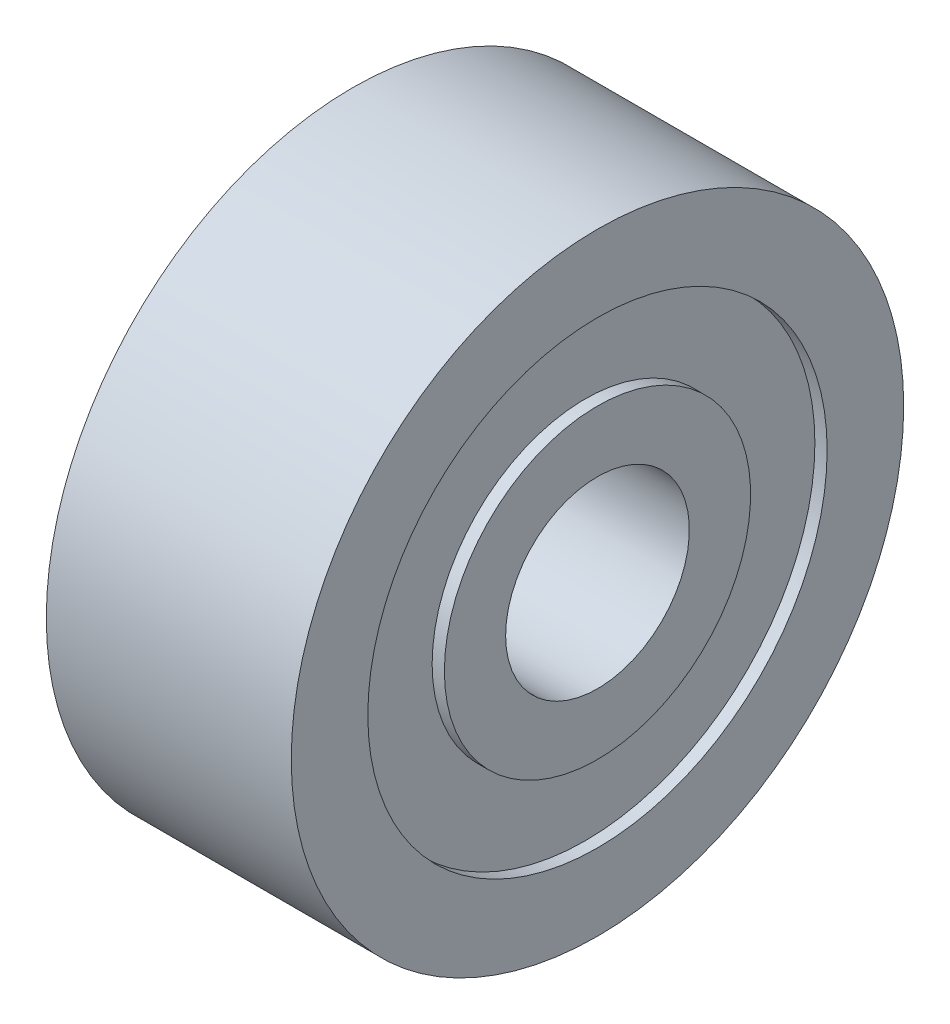
SolidWorks part; units mm, degrees
material "Acier allié"
ref_plane "Plan de face" through (0, 0, 0) normal (0, 0, 1) x (1, 0, 0)
ref_plane "Plan de dessus" through (0, 0, 0) normal (0, 1, 0) x (1, 0, 0)
ref_plane "Plan de droite" through (0, 0, 0) normal (1, 0, 0) x (0, 0, -1)
sketch "Esquisse1" plane through (0, 0, 0) normal (0, 0, 1) x (1, 0, 0)
  line L1 (-2, 2.5) -> (-1.8, 2.5)
  line L2 (-2, 2.5) -> (-2, 1.5)
  line L3 (-2, 1.5) -> (2, 1.5)
  line L4 (2, 2.5) -> (2, 1.5)
  line L5 (1.8, 3.75) -> (2, 3.75)
  line L6 (-1.8, 3.75) -> (-1.8, 2.5)
  line L8 (1.8, 3.75) -> (1.8, 2.5)
  line L9 (-2, 5) -> (2, 5)
  line L10 (-2, 5) -> (-2, 3.75)
  line L11 (-2, 3.75) -> (-1.8, 3.75)
  line L12 (2, 5) -> (2, 3.75)
  line L15 (-2, 0) -> (2, 0) construction
  line L16 (1.8, 2.5) -> (2, 2.5)
  point P18 (0, 1.5)
  dimension "D7" = 1.25
  dimension "D1" = 10
  dimension "D2" = 4
  dimension "D3" = 3
  dimension "D4" = 5
  dimension "D5" = 7.5
  dimension "D6" = 0.2
  dimension "D8" = 1
revolve "Révolution1" add sketch "Esquisse1" angle 360 about L15
